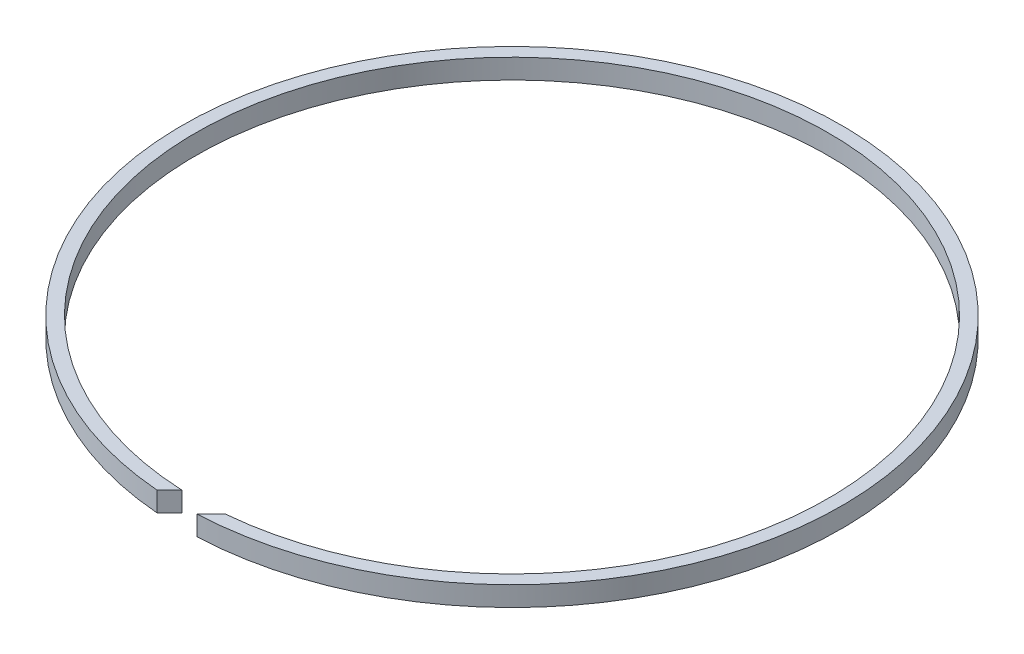
SolidWorks part; units mm, degrees
ref_plane "Płaszczyzna przednia" through (0, 0, 0) normal (0, 0, 1) x (1, 0, 0)
ref_plane "Płaszczyzna górna" through (0, 0, 0) normal (0, 1, 0) x (1, 0, 0)
ref_plane "Płaszczyzna prawa" through (0, 0, 0) normal (1, 0, 0) x (0, 0, -1)
sketch "Szkic1" plane through (0, 0, 0) normal (0, 1, 0) x (1, 0, 0)
  circle A0 centre (0, 0) radius 63.5
  circle A1 centre (0, 0) radius 60.96
  dimension "D1" = 127
  dimension "D2" = 121.92
extrude "Dodanie-wyciągnięcie1" add sketch "Szkic1" along normal blind 3.81
sketch "Szkic2" plane through (0, 3.81, 0) normal (0, 1, 0) x (1, 0, 0)
  line L4 (3.9451, -58.2849) -> (7.9451, -58.2849)
  line L5 (7.9451, -58.2849) -> (0.0825, -66.1475)
  line L6 (0.0825, -66.1475) -> (-7.9175, -66.1475)
  line L7 (-7.9175, -66.1475) -> (-0.0549, -58.2849)
  line L8 (3.9451, -58.2849) -> (-0.0549, -58.2849)
  dimension "D1" = 4
  dimension "D2" = 8
extrude "Wytnij-wyciągnięcie1" cut sketch "Szkic2" against normal through all
